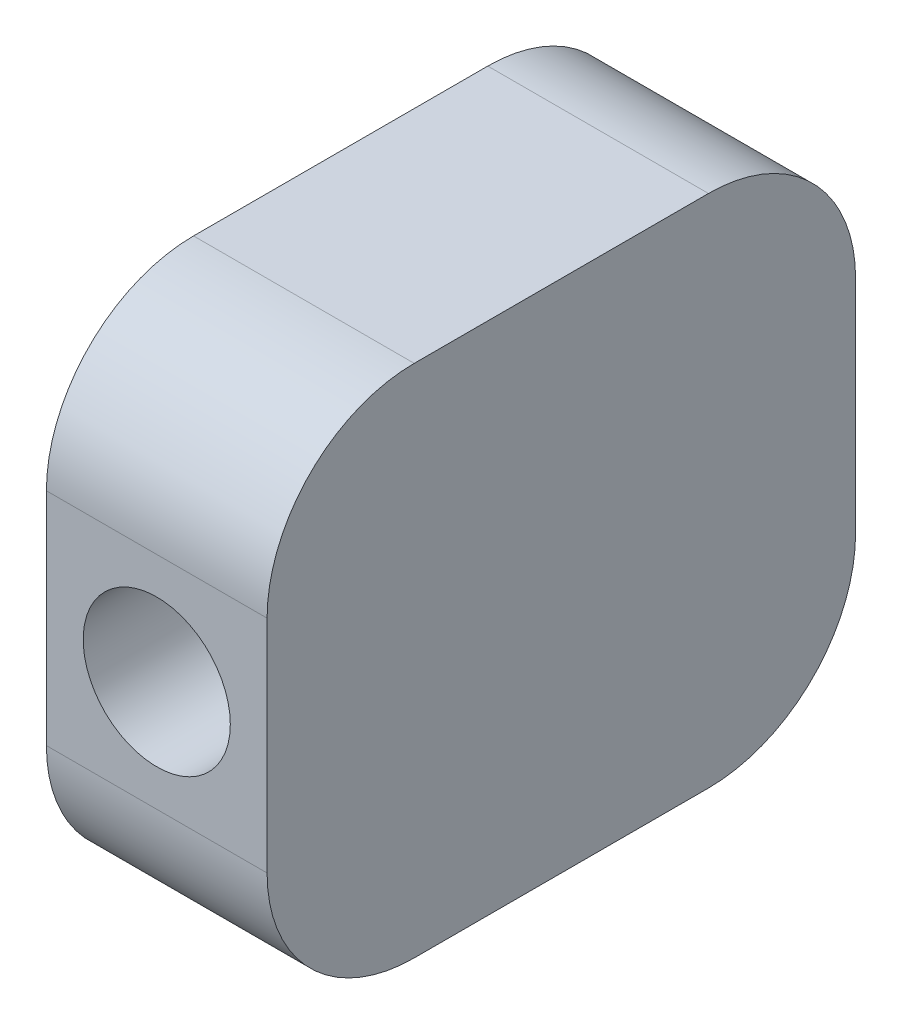
SolidWorks part; units mm, degrees
ref_plane "Front Plane" through (0, 0, 0) normal (0, 0, 1) x (1, 0, 0)
ref_plane "Top Plane" through (0, 0, 0) normal (0, 1, 0) x (1, 0, 0)
ref_plane "Right Plane" through (0, 0, 0) normal (1, 0, 0) x (0, 0, -1)
sketch "Sketch1" plane through (0, 0, 0) normal (1, 0, 0) x (0, 0, -1)
  line L1 (-40, -35) -> (40, -35)
  line L2 (-40, -35) -> (-40, 35)
  line L3 (-40, 35) -> (40, 35)
  line L4 (40, -35) -> (40, 35)
  line L5 (-40, -35) -> (40, 35) construction
  line L6 (-40, 35) -> (40, -35) construction
  point P0 (0, 0)
  dimension "D1" = 80
  dimension "D2" = 70
extrude "Boss-Extrude1" add sketch "Sketch1" along normal blind 30
sketch "Sketch2" plane through (0, 0, 40) normal (0, 0, 1) x (1, 0, 0)
  line L0 (0, 0) -> (30, 0) construction
  line L1 (30, 35) -> (30, -35) construction
  circle A0 centre (15, 0) radius 10
extrude "Cut-Extrude1" cut sketch "Sketch2" against normal blind 50
fillet "Fillet1" radius 20 1 edges at (15, 35, -40)
fillet "Fillet2" radius 20 1 edges at (15, -35, -40)
fillet "Fillet3" radius 20 1 edges at (15, -35, 40)
fillet "Fillet4" radius 20 1 edges at (15, 35, 40)
